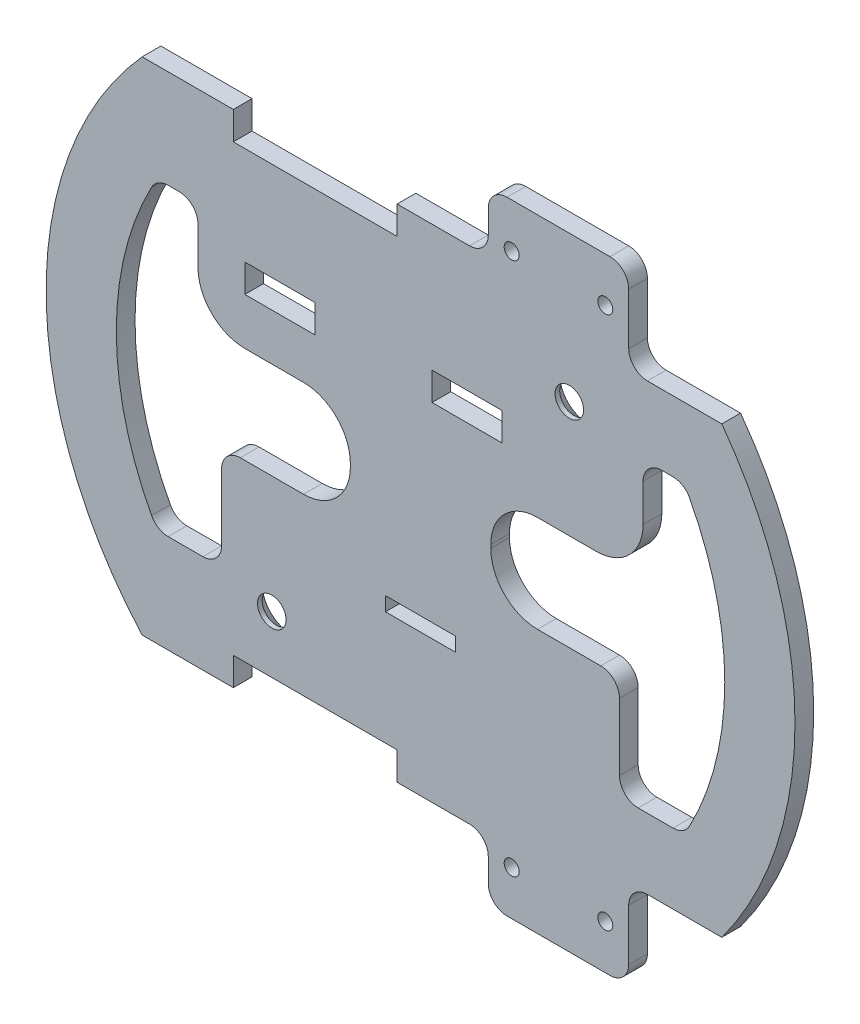
SolidWorks part; units mm, degrees
material "Acrílico (médio-alto impacto)"
ref_plane "Plano frontal" through (0, 0, 0) normal (0, 0, 1) x (1, 0, 0)
ref_plane "Plano superior" through (0, 0, 0) normal (0, 1, 0) x (1, 0, 0)
ref_plane "Plano direito" through (0, 0, 0) normal (1, 0, 0) x (0, 0, -1)
sketch "Esboço1" plane through (0, 0, 0) normal (0, 0, 1) x (1, 0, 0)
  line L0 (80, 0) -> (0, 0) construction
  line L1 (-80, -66.5) -> (80, -66.5)
  line L2 (-80, -66.5) -> (-80, 66.5)
  line L3 (-80, 66.5) -> (80, 66.5)
  line L4 (80, -66.5) -> (80, 66.5)
  line L5 (-80, -66.5) -> (80, 66.5) construction
  line L6 (-80, 66.5) -> (80, -66.5) construction
  line L7 (80, 47.5) -> (-80, 47.5) construction
  line L8 (80, -47.5) -> (-80, -47.5) construction
  line L9 (14.4719, 66.5) -> (14.4719, 53.5)
  line L10 (0, 0) -> (0, 66.5) construction
  line L11 (44.4719, 47.5) -> (44.4719, 66.5)
  line L12 (44.4719, -47.5) -> (44.4719, -66.5)
  line L13 (14.4719, -66.5) -> (14.4719, -53.5)
  line L14 (14.4719, 53.5) -> (-59.479, 53.5)
  line L15 (14.4719, -53.5) -> (-59.479, -53.5)
  line L16 (-5.0035, 47.5) -> (-40.0035, 47.5)
  line L17 (-5.0035, 47.5) -> (-5.0035, 53.5)
  line L18 (-31.7837, -35.2994) -> (31.7837, 35.2994) construction
  line L19 (-42.5, -20.2) -> (-42.5, -14.2) construction
  line L20 (-7.5, -20.2) -> (7.5, -20.2)
  line L21 (-7.5, -20.2) -> (-7.5, -23.2)
  line L22 (-7.5, -23.2) -> (7.5, -23.2)
  line L23 (7.5, -20.2) -> (7.5, -23.2)
  line L24 (-7.5, -20.2) -> (7.5, -23.2) construction
  line L25 (-7.5, -23.2) -> (7.5, -20.2) construction
  line L26 (-37.55, 26.5) -> (-22.55, 26.5)
  line L27 (-37.55, 26.5) -> (-37.55, 20.5)
  line L28 (-37.55, 20.5) -> (-22.55, 20.5)
  line L29 (-22.55, 26.5) -> (-22.55, 20.5)
  line L30 (-37.55, 26.5) -> (-22.55, 20.5) construction
  line L31 (-37.55, 20.5) -> (-22.55, 26.5) construction
  line L32 (17.45, 20.5) -> (2.45, 20.5)
  line L33 (17.45, 20.5) -> (17.45, 26.5)
  line L34 (17.45, 26.5) -> (2.45, 26.5)
  line L35 (2.45, 20.5) -> (2.45, 26.5)
  line L36 (17.45, 20.5) -> (2.45, 26.5) construction
  line L37 (17.45, 26.5) -> (2.45, 20.5) construction
  line L38 (-42.5, -14.2) -> (42.5, -14.2) construction
  line L39 (42.5, -14.2) -> (42.5, -20.2) construction
  line L40 (42.5, -20.2) -> (-42.5, -20.2) construction
  line L41 (-56.2917, 32.5) -> (-47.55, 32.5)
  line L42 (-47.55, 32.5) -> (-47.55, 10.5)
  line L43 (-47.55, 10.5) -> (-15, 10.5)
  line L44 (-15, 10.5) -> (-15, -10.2)
  line L47 (-42.5, -32.5) -> (-56.2917, -32.5)
  line L48 (-42.5, -32.5) -> (-42.5, -10.2)
  line L49 (-42.5, -10.2) -> (-15, -10.2)
  line L50 (15, -10.2) -> (15, 10.5)
  line L51 (15, 10.5) -> (47.55, 10.5)
  line L52 (47.55, 10.5) -> (47.55, 32.5)
  line L53 (47.55, 32.5) -> (56.2917, 32.5)
  line L54 (56.2917, -32.5) -> (42.5, -32.5)
  line L55 (15, -10.2) -> (42.5, -10.2)
  line L56 (42.5, -10.2) -> (42.5, -32.5)
  line L57 (15, 10.5) -> (-15, 10.5) construction
  line L58 (-21.0674, -35.2994) -> (-42.5, -35.2994) construction
  line L59 (-5.0035, 53.5) -> (-40.0035, 53.5)
  line L60 (-40.0035, 47.5) -> (-40.0035, 53.5)
  line L61 (-5.0035, 47.5) -> (-40.0035, 53.5) construction
  line L62 (-5.0035, 53.5) -> (-40.0035, 47.5) construction
  line L63 (-5.0035, -53.5) -> (-40.0035, -53.5)
  line L64 (-40.0035, -47.5) -> (-40.0035, -53.5)
  line L65 (-5.0035, -47.5) -> (-40.0035, -47.5)
  line L66 (-5.0035, -47.5) -> (-5.0035, -53.5)
  line L67 (24.9009, 47.5) -> (24.9009, 66.5) construction
  line L69 (44.4719, 47.5) -> (64.372, 47.5)
  line L70 (44.4719, -47.5) -> (64.372, -47.5)
  circle A0 centre (0, 0) radius 80
  circle A1 centre (-31.7837, -35.2994) radius 3.05
  circle A2 centre (31.7837, 35.2994) radius 3.05
  circle A3 centre (19.4719, 57) radius 1.6
  circle A8 centre (19.4719, -57) radius 1.6
  arc A9 (-56.2917, -32.5) -> (-56.2917, 32.5) centre (0, 0) cw
  arc A10 (56.2917, -32.5) -> (56.2917, 32.5) centre (0, 0) ccw
  circle A11 centre (39.4719, 57) radius 1.6
  circle A12 centre (39.4719, -57) radius 1.6
  point P0 (0, 0)
  point P17 (-22.5035, 50.5)
  point P22 (44.4719, 66.5)
  point P34 (-30.05, 23.5)
  point P44 (0, -21.7)
  point P53 (9.95, 23.5)
  point P58 (0, -20.2)
  point P65 (-65, 0)
  point P80 (0, 10.5)
  point P83 (24.9009, 57)
  point P84 (-22.5035, 53.5)
  dimension "D6" = 6.1
  dimension "D7" = 6
  dimension "D18" = 15
  dimension "D25" = 3.2
  dimension "D1" = 95
  dimension "D2" = 19
  dimension "D3" = 160
  dimension "D4" = 95
  dimension "D5" = 48
  dimension "D8" = 5
  dimension "D9" = 3
  dimension "D10" = 6
  dimension "D11" = 15
  dimension "D12" = 20.2
  dimension "D13" = 40.7
  dimension "D14" = 25
  dimension "D15" = 2.45
  dimension "D16" = 85
  dimension "D17" = 35
  dimension "D19" = 10
  dimension "D20" = 10
  dimension "D21" = 10
  dimension "D22" = 30
  dimension "D23" = 30
  dimension "D24" = 5
  dimension "D26" = 15
extrude "Ressalto-extrusão1" add sketch "Esboço1" along normal blind 4
chamfer "Chanfro1" distance 3 angle 45 2 edges at (34.8337, 35.2994, 0) (-28.7337, -35.2994, 0)
fillet "Filete1" radius 4 18 edges at (56.2917, 32.5, 2) (47.55, 32.5, 2) (42.5, -32.5, 2) (56.2917, -32.5, 2) (-42.5, -32.5, 2) (-56.2917, -32.5, 2) (42.5, -10.2, 2) (-42.5, -10.2, 2) (-47.55, 32.5, 2) (-56.2917, 32.5, 2) (14.4719, -53.5, 2) (14.4719, 53.5, 2) (44.4719, 47.5, 2) (44.4719, -47.5, 2) (14.4719, 66.5, 2) (44.4719, 66.5, 2) (44.4719, -66.5, 2) (14.4719, -66.5, 2)
fillet "Filete2" radius 10 6 edges at (15, -10.2, 2) (-15, -10.2, 2) (-15, 10.5, 2) (15, 10.5, 2) (47.55, 10.5, 2) (-47.55, 10.5, 2)
